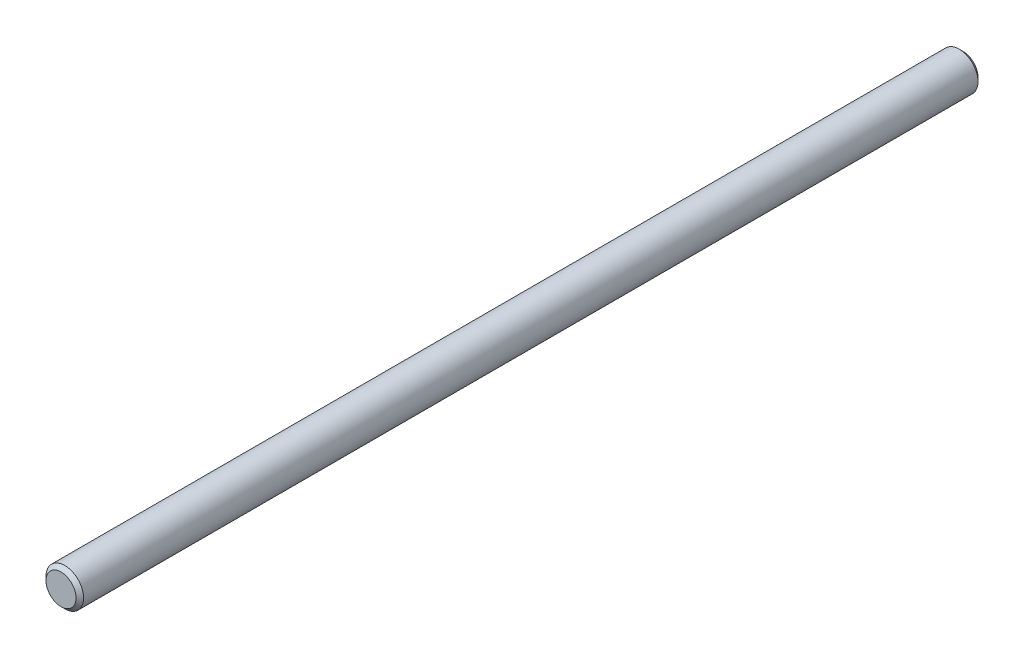
SolidWorks part; units mm, degrees
material "Plain Carbon Steel"
ref_plane "Front Plane" through (0, 0, 0) normal (0, 0, 1) x (1, 0, 0)
ref_plane "Top Plane" through (0, 0, 0) normal (0, 1, 0) x (1, 0, 0)
ref_plane "Right Plane" through (0, 0, 0) normal (1, 0, 0) x (0, 0, -1)
sketch "Sketch1" plane through (0, 0, 0) normal (0, 0, 1) x (1, 0, 0)
  circle A0 centre (0, 0) radius 2.5
  dimension "D1" = 5
extrude "Boss-Extrude1" add sketch "Sketch1" along normal mid plane 120
chamfer "Chamfer1" distance 0.5 angle 45 2 edges at (2.5, 0, -60) (2.5, 0, 60)
